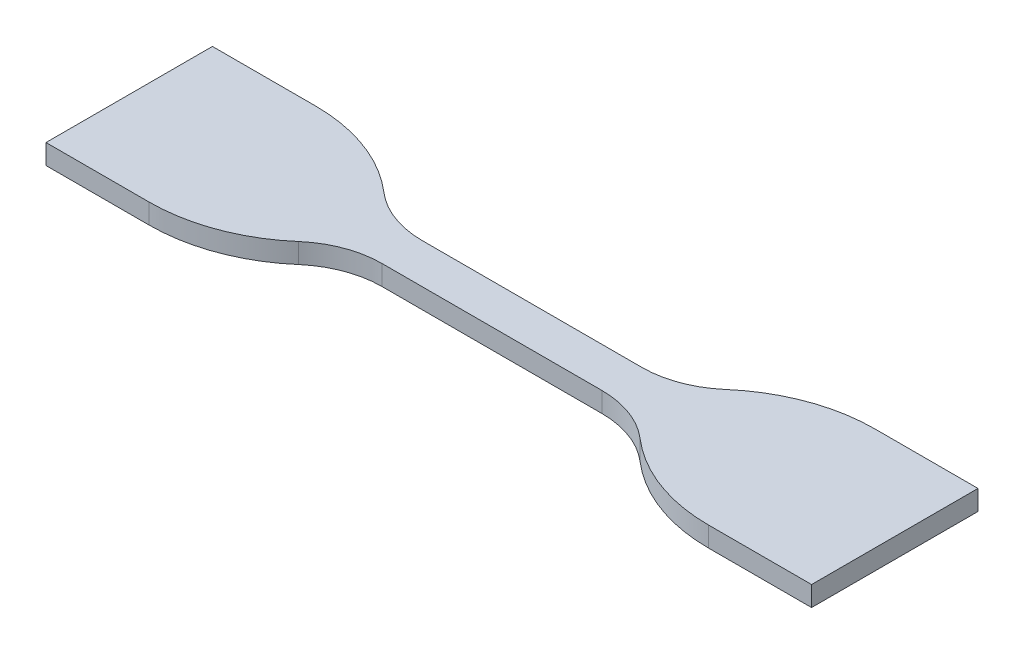
SolidWorks part; units mm, degrees
ref_plane "Front Plane" through (0, 0, 0) normal (0, 0, 1) x (1, 0, 0)
ref_plane "Top Plane" through (0, 0, 0) normal (0, 1, 0) x (1, 0, 0)
ref_plane "Right Plane" through (0, 0, 0) normal (1, 0, 0) x (0, 0, -1)
sketch "Sketch1" plane through (0, 0, 0) normal (0, 1, 0) x (1, 0, 0)
  line L0 (0, 0) -> (78.467, 0) construction
  line L1 (0, 0) -> (0, 31.5179) construction
  line L2 (0, 3) -> (16.5, 3)
  line L3 (42.0098, 12.5) -> (57.5, 12.5)
  line L4 (57.5, 12.5) -> (57.5, 0)
  line L5 (57.5, 0) -> (0, 0)
  line L6 (0, 0) -> (0, 3)
  arc A0 (16.5, 3) -> (25.6574, 6.4103) centre (16.5, 17) ccw
  arc A1 (25.6574, 6.4103) -> (42.0098, 12.5) centre (42.0098, -12.5) cw
  point P11 (0, 2.3607)
  dimension "D4" = 14
  dimension "D5" = 25
  dimension "D1" = 115
  dimension "D2" = 25
  dimension "D3" = 6
  dimension "D6" = 33
extrude "Boss-Extrude1" add sketch "Sketch1" along normal mid plane 3
mirror "Mirror1" about plane through (0, 0, 0) normal (1, 0, 0) of "Boss-Extrude1"
scale "Scale1" scale about centroid uniform scaling yes scale factor 0.5
